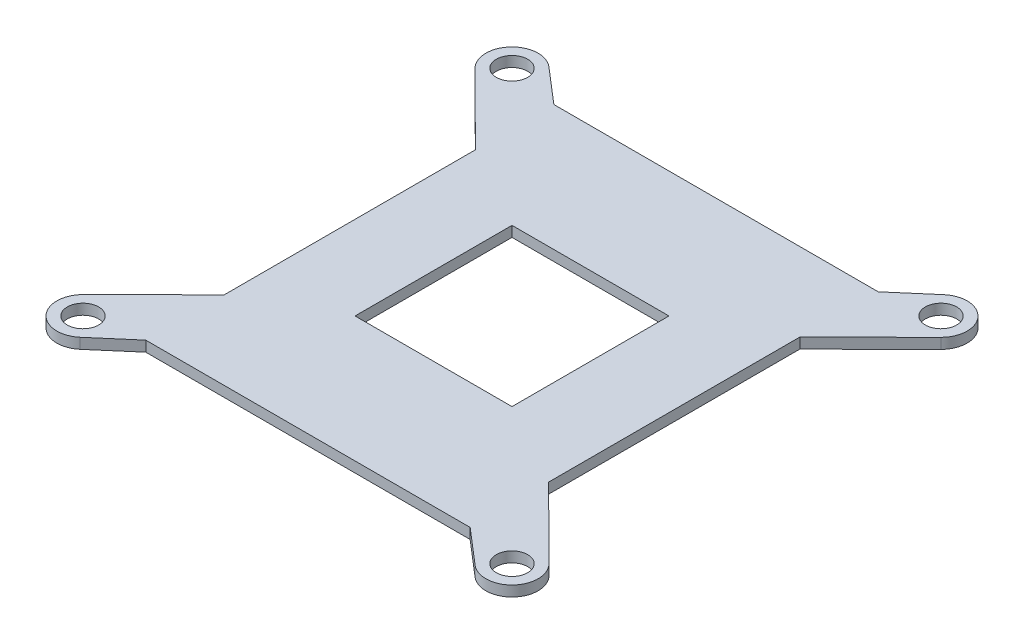
SolidWorks part; units mm, degrees
ref_plane "Alzado" through (0, 0, 0) normal (0, 0, 1) x (1, 0, 0)
ref_plane "Planta" through (0, 0, 0) normal (0, 1, 0) x (1, 0, 0)
ref_plane "Vista lateral" through (0, 0, 0) normal (1, 0, 0) x (0, 0, -1)
sketch "Croquis1" plane through (0, 0, 0) normal (0, 1, 0) x (1, 0, 0)
  line L0 (0, 41) -> (0, -41) construction
  line L1 (-41, 41) -> (41, 41) construction
  line L2 (-41, 41) -> (-41, -41) construction
  line L3 (-41, -41) -> (41, -41) construction
  line L4 (41, 41) -> (41, -41) construction
  line L5 (-31, 39) -> (-37.7415, 44.7924)
  line L6 (-31, 39) -> (31, 39)
  line L7 (-31, 24) -> (-31, -24)
  line L8 (-31, -39) -> (31, -39)
  line L9 (31, 24) -> (31, -24)
  line L10 (-31, 39) -> (31, -39) construction
  line L11 (-31, -39) -> (31, 39) construction
  line L12 (31, 39) -> (37.7415, 44.7924)
  line L13 (31, -39) -> (37.7415, -44.7924)
  line L14 (-31, -39) -> (-37.7415, -44.7924)
  line L15 (-31, -24) -> (-44.5262, -37.4552)
  line L16 (31, -24) -> (44.5262, -37.4552)
  line L17 (31, 24) -> (44.5262, 37.4552)
  line L18 (-31, 24) -> (-44.5262, 37.4552)
  line L20 (-15, 15) -> (15, 15)
  line L21 (-15, 15) -> (-15, -15)
  line L22 (-15, -15) -> (15, -15)
  line L23 (15, 15) -> (15, -15)
  line L24 (-15, 15) -> (15, -15) construction
  line L25 (-15, -15) -> (15, 15) construction
  circle A0 centre (-41, 41) radius 3
  circle A1 centre (41, 41) radius 3
  circle A2 centre (41, -41) radius 3
  circle A3 centre (-41, -41) radius 3
  arc A4 (-37.7415, 44.7924) -> (-44.5262, 37.4552) centre (-41, 41) ccw
  arc A5 (44.5262, 37.4552) -> (37.7415, 44.7924) centre (41, 41) ccw
  arc A6 (37.7415, -44.7924) -> (44.5262, -37.4552) centre (41, -41) ccw
  arc A7 (-44.5262, -37.4552) -> (-37.7415, -44.7924) centre (-41, -41) ccw
  point P4 (0, 0)
  point P8 (0, 0)
  point P10 (0, 41)
  point P11 (0, -41)
  point P14 (0, 0)
  dimension "D3" = 6
  dimension "D10" = 10
  dimension "D15" = 30
  dimension "D1" = 82
  dimension "D2" = 82
  dimension "D8" = 62
  dimension "D9" = 78
  dimension "D11" = 15
  dimension "D12" = 15
  dimension "D13" = 15
  dimension "D14" = 15
  dimension "D16" = 30
  dimension "D4" = 2
  dimension "D5" = 2
  dimension "D6" = 2
  dimension "D7" = 2
extrude "Saliente-Extruir1" add sketch "Croquis1" along normal blind 2
